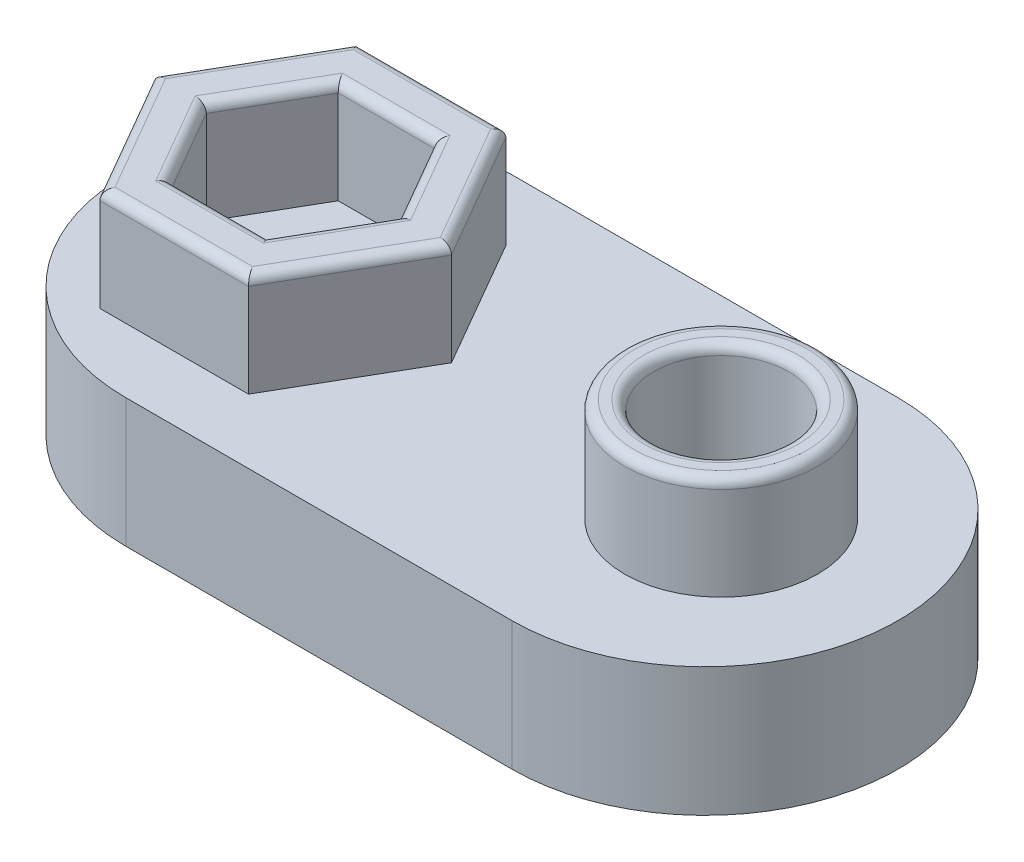
SolidWorks part; units mm, degrees
ref_plane "Спереди" through (0, 0, 0) normal (0, 0, 1) x (1, 0, 0)
ref_plane "Сверху" through (0, 0, 0) normal (0, 1, 0) x (1, 0, 0)
ref_plane "Справа" through (0, 0, 0) normal (1, 0, 0) x (0, 0, -1)
sketch "Эскиз1" plane through (0, 0, 0) normal (0, 1, 0) x (1, 0, 0)
  line L0 (-12, 0) -> (0, 0) construction
  line L5 (0, 0) -> (0, 6) construction
  line L6 (6, 6) -> (-6, 6)
  line L7 (6, -6) -> (-6, -6)
  arc A0 (-6, -6) -> (-6, 6) centre (-6, 0) cw
  arc A1 (6, -6) -> (6, 6) centre (6, 0) ccw
  point P11 (0, 0)
  dimension "D1" = 12
  dimension "D2" = 6
extrude "Бобышка-Вытянуть1" add sketch "Эскиз1" along normal blind 4
sketch "Эскиз2" plane through (0, 4, 0) normal (0, 1, 0) x (1, 0, 0)
  line L1 (-1.8812, 0) -> (-4.1906, 4)
  line L2 (-4.1906, 4) -> (-8.8094, 4)
  line L3 (-8.8094, 4) -> (-11.1188, 0)
  line L4 (-11.1188, 0) -> (-8.8094, -4)
  line L5 (-8.8094, -4) -> (-4.1906, -4)
  line L6 (-4.1906, -4) -> (-1.8812, 0)
  line L7 (-3.4978, 0) -> (-4.9989, 2.6)
  line L8 (-4.9989, 2.6) -> (-8.0011, 2.6)
  line L9 (-8.0011, 2.6) -> (-9.5022, 0)
  line L10 (-9.5022, 0) -> (-8.0011, -2.6)
  line L11 (-8.0011, -2.6) -> (-4.9989, -2.6)
  line L12 (-4.9989, -2.6) -> (-3.4978, 0)
  circle A0 centre (6.5, 0) radius 3
  circle A1 centre (6.5, 0) radius 2.1
  circle A2 centre (-6.5, 0) radius 4 construction
  circle A3 centre (-6.5, 0) radius 2.6 construction
  point P3 (0, 0)
  point P20 (0, 0)
  point P21 (0, 0)
  dimension "D2" = 6
  dimension "D3" = 4.2
  dimension "D1" = 6.5
  dimension "D4" = 6.5
  dimension "D5" = 8
  dimension "D6" = 5.2
extrude "Бобышка-Вытянуть2" add sketch "Эскиз2" along normal blind 3.2
fillet "Скругление1" radius 0.3 14 edges at (6.5, 7.2, 2.1) (6.5, 7.2, 3) (-6.5, 7.2, -2.6) (-8.7517, 7.2, -1.3) (-8.7517, 7.2, 1.3) (-6.5, 7.2, 2.6) (-4.2483, 7.2, 1.3) (-4.2483, 7.2, -1.3) (-6.5, 7.2, 4) (-9.9641, 7.2, 2) (-9.9641, 7.2, -2) (-6.5, 7.2, -4) (-3.0359, 7.2, -2) (-3.0359, 7.2, 2)
